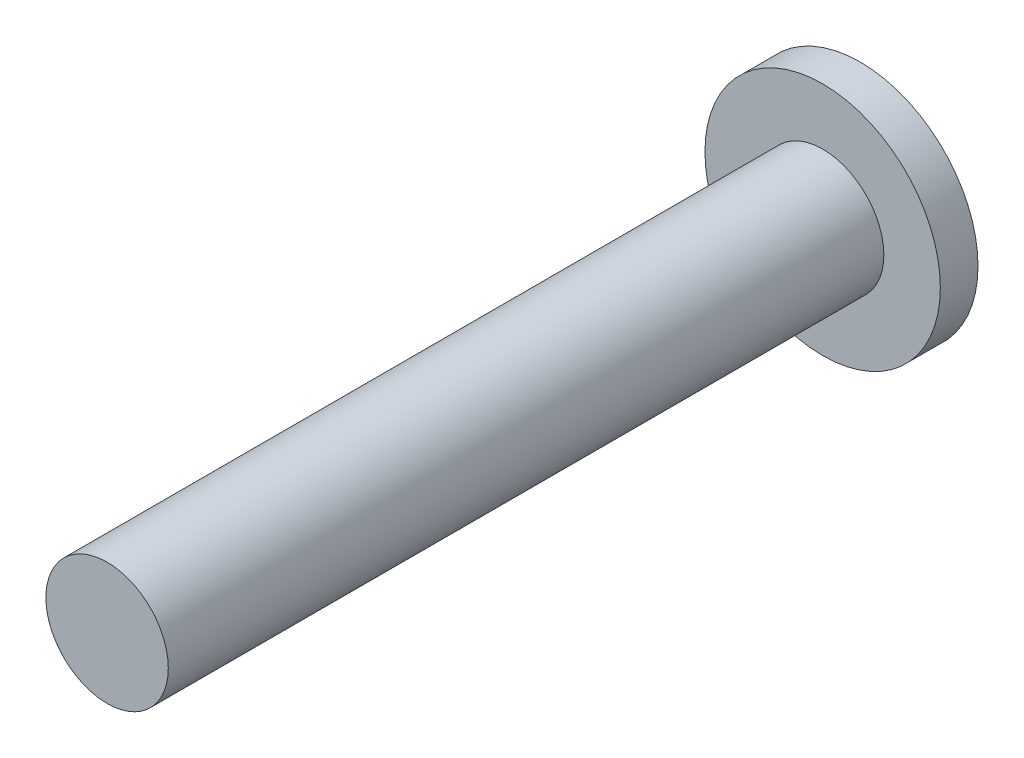
SolidWorks part; units mm, degrees
ref_plane "Front Plane" through (0, 0, 0) normal (0, 0, 1) x (1, 0, 0)
ref_plane "Top Plane" through (0, 0, 0) normal (0, 1, 0) x (1, 0, 0)
ref_plane "Right Plane" through (0, 0, 0) normal (1, 0, 0) x (0, 0, -1)
sketch "Sketch1" plane through (0, 0, 0) normal (0, 0, 1) x (1, 0, 0)
  circle A0 centre (0, 0) radius 12.5
  dimension "D1" = 25
extrude "Boss-Extrude1" add sketch "Sketch1" along normal blind 4
sketch "Sketch2" plane through (0, 0, 0) normal (0, 0, 1) x (1, 0, 0)
  circle A0 centre (0, 0) radius 6.5
  dimension "D1" = 13
extrude "Boss-Extrude2" add sketch "Sketch2" along normal blind 80
